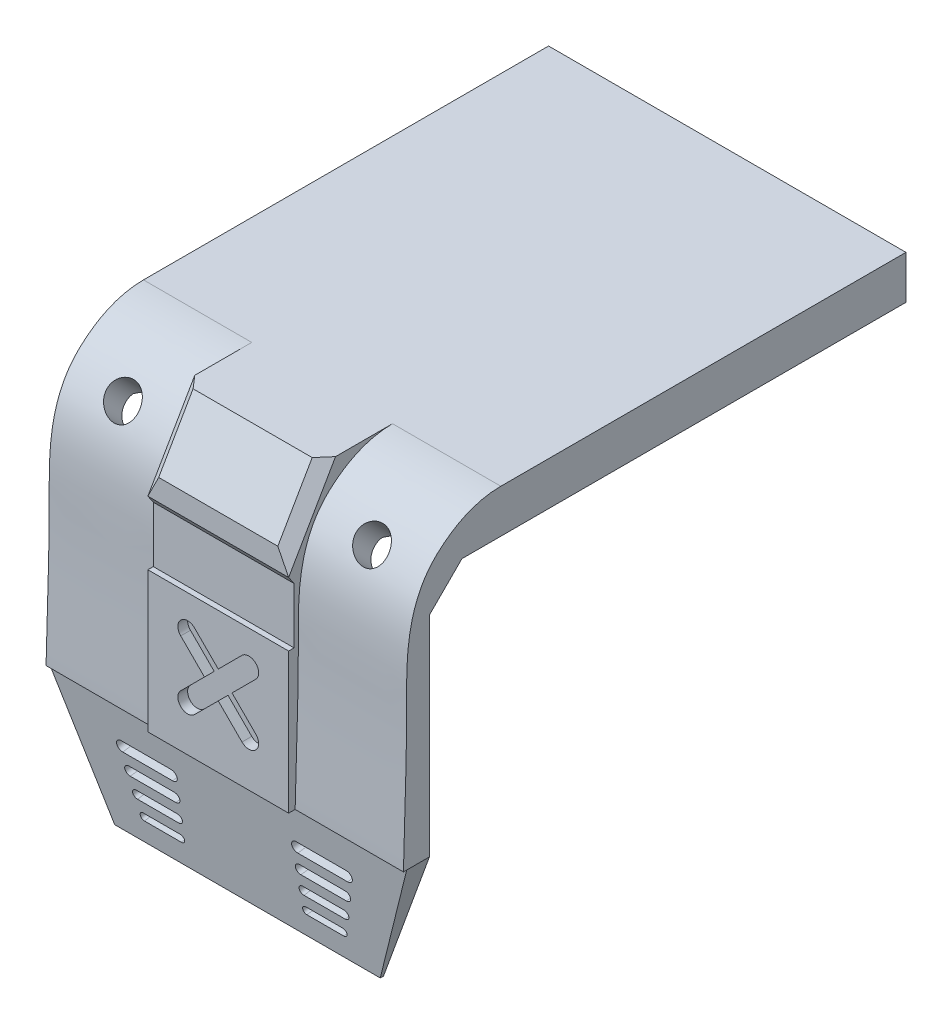
SolidWorks part; units mm, degrees
ref_plane "前视基准面" through (0, 0, 0) normal (0, 0, 1) x (1, 0, 0)
ref_plane "上视基准面" through (0, 0, 0) normal (0, 1, 0) x (1, 0, 0)
ref_plane "右视基准面" through (0, 0, 0) normal (1, 0, 0) x (0, 0, -1)
sketch "草图1" plane through (0, 0, 0) normal (0, 1, 0) x (1, 0, 0)
  line L1 (16.5, -12) -> (-16.5, -12)
  line L2 (16.5, -12) -> (16.5, 12)
  line L3 (16.5, 12) -> (-16.5, 12)
  line L4 (-16.5, -12) -> (-16.5, 12)
  line L5 (16.5, -12) -> (-16.5, 12) construction
  line L6 (16.5, 12) -> (-16.5, -12) construction
  point P0 (0, 0)
  dimension "D1" = 33
  dimension "D2" = 24
extrude "凸台-拉伸1" add sketch "草图1" along normal blind 38
sketch "草图2" plane through (-16.5, 0, 0) normal (-1, 0, 0) x (0, 0, 1)
  line L0 (-12, 33) -> (9, 33)
  line L1 (-12, 38) -> (-12, 0) construction
  line L2 (9, 33) -> (9, 0)
  line L3 (-12, 0) -> (12, 0) construction
  line L4 (9, 0) -> (-12, 0)
  line L5 (-12, 0) -> (-12, 33)
  line L6 (-12, 38) -> (12, 38) construction
  line L7 (12, 38) -> (12, 0) construction
  dimension "D1" = 5
  dimension "D2" = 3
extrude "切除-拉伸1" cut sketch "草图2" against normal blind 35
chamfer "倒角1" distance 5.5 angle 30 1 edges at (0, 38, 12)
chamfer "倒角2" distance 2 angle 45 1 edges at (0, 33, 9)
chamfer "倒角3" distance 1 angle 45 2 edges at (16.5, 33, -2.5) (-16.5, 33, -2.5)
sketch "草图3" plane through (-16.5, 0, 0) normal (-1, 0, 0) x (0, 0, 1)
  line L0 (12, 11.6526) -> (11.1, 11.6526)
  line L1 (12, 32.5) -> (12, 0) construction
  line L2 (11.1, 11.6526) -> (9.3, 0)
  line L3 (9, 0) -> (12, 0) construction
  line L4 (9.3, 0) -> (12, 0)
  line L5 (12, 0) -> (12, 11.6526)
  dimension "D1" = 0.9
  dimension "D2" = 0.3
extrude "切除-拉伸2" cut sketch "草图3" against normal blind 35
sketch "草图4" plane through (-16.5, 0, 0) normal (-1, 0, 0) x (0, 0, 1)
  line L0 (-12, 38) -> (8.8246, 38) construction
  line L1 (2.4074, 38) -> (8.8246, 38)
  line L2 (8.8246, 38) -> (12, 32.5)
  line L6 (12, 32.5) -> (12, 11.6526)
  line L7 (12, 11.6526) -> (11.4, 11.6526)
  spline S0 degree 3 poles (2.4074, 38) (4.9446, 38) (7.5567, 36.3443) (10.7301, 32.9821) (11.1498, 28.4683) (11.0414, 20.8883) (11.4, 13.3386) (11.4, 11.6526) knots 0 0 0 0 0.11289 0.156477 0.404831 0.492287 1 1 1 1
  dimension "D1" = 0.6
extrude "切除-拉伸3" cut sketch "草图4" against normal blind 10
mirror "镜向1" about plane through (0, 0, 0) normal (1, 0, 0) of "切除-拉伸3"
sketch "草图6" plane through (0, 0, 9) normal (0, 0, -1) x (-1, 0, 0)
  line L0 (19.0092, 11.6526) -> (-21.5597, 11.6526) construction
  line L1 (-6.5, 11.6526) -> (6.5, 11.6526) construction
  line L2 (16.5, 11.6526) -> (12.2588, 0)
  line L3 (16.5, 0) -> (-16.5, 0) construction
  line L4 (12.2588, 0) -> (16.5, 0)
  line L5 (16.5, 0) -> (16.5, 11.6526)
  line L6 (0, 0) -> (0, 18.5303) construction
  line L7 (-12.2588, 0) -> (-16.5, 0)
  line L8 (-16.5, 11.6526) -> (-12.2588, 0)
  line L9 (-16.5, 0) -> (-16.5, 11.6526)
  line L10 (16.5, 0) -> (16.5, 31) construction
  dimension "D1" = 20
extrude "切除-拉伸4" cut sketch "草图6" against normal through all
sketch "草图7" plane through (0, 0, 12) normal (0, 0, 1) x (1, 0, 0)
  line L0 (-2.8284, 15.8242) -> (2.8284, 21.4811) construction
  line L1 (-3.4648, 16.4606) -> (2.192, 22.1175)
  line L2 (-2.192, 15.1878) -> (3.4648, 20.8447)
  line L3 (-2.8284, 21.4811) -> (2.8284, 15.8242) construction
  line L4 (-2.192, 22.1175) -> (3.4648, 16.4606)
  line L5 (-3.4648, 20.8447) -> (2.192, 15.1878)
  line L6 (0, 11.6526) -> (0, 25.4332) construction
  line L7 (6.5, 11.6526) -> (-6.5, 11.6526) construction
  arc A0 (-3.4648, 16.4606) -> (-2.192, 15.1878) centre (-2.8284, 15.8242) ccw
  arc A1 (3.4648, 20.8447) -> (2.192, 22.1175) centre (2.8284, 21.4811) ccw
  arc A2 (-2.192, 22.1175) -> (-3.4648, 20.8447) centre (-2.8284, 21.4811) ccw
  arc A3 (2.192, 15.1878) -> (3.4648, 16.4606) centre (2.8284, 15.8242) ccw
  point P2 (0, 18.6526)
  point P7 (0, 18.6526)
  dimension "D1" = 8
  dimension "D2" = 7
  dimension "D3" = 1.8
sketch "草图8" plane through (0, 0, -12) normal (0, 0, -1) x (-1, 0, 0)
  line L6 (-16.5, 38) -> (-16.5, 34)
  line L7 (-16.5, 34) -> (-15.5, 33)
  line L8 (-15.5, 33) -> (15.5, 33)
  line L9 (15.5, 33) -> (16.5, 34)
  line L10 (16.5, 34) -> (16.5, 38)
  line L11 (16.5, 38) -> (-16.5, 38)
  line L12 (-16.5, 38) -> (-16.5, 34)
  line L13 (-16.5, 34) -> (-15.5, 33)
  line L14 (-15.5, 33) -> (15.5, 33)
  line L15 (15.5, 33) -> (16.5, 34)
  line L16 (16.5, 34) -> (16.5, 38)
  line L17 (16.5, 38) -> (-16.5, 38)
  dimension "D1" = 0
extrude "凸台-拉伸4" add sketch "草图8" along normal blind 23
chamfer "倒角4" distance 1 angle 45 2 edges at (-6.5, 35.25, 10.4123) (6.5, 35.25, 10.4123)
sketch "草图9" plane through (0, -1.4031, 9.0833) normal (0, -0.1527, 0.9883) x (1, 0, 0)
  line L0 (-10.3833, 9.3197) -> (-5.7833, 9.3197) construction
  line L3 (-10.3833, 9.8197) -> (-5.7833, 9.8197)
  line L6 (-10.3833, 8.8197) -> (-5.7833, 8.8197)
  line L9 (-7.0299, -0.703) -> (-8.4476, 12.7851) construction
  line L12 (0, 1.4197) -> (0, 15.4722) construction
  line L13 (12.2588, 1.4197) -> (-12.2588, 1.4197) construction
  line L14 (-9.9784, 7.3697) -> (-5.7784, 7.3697) construction
  line L15 (-9.9784, 7.8197) -> (-5.7784, 7.8197)
  line L16 (-9.9784, 6.9197) -> (-5.7784, 6.9197)
  line L17 (-9.5839, 5.5197) -> (-5.7839, 5.5197) construction
  line L18 (-9.5839, 5.9197) -> (-5.7839, 5.9197)
  line L19 (-9.5839, 5.1197) -> (-5.7839, 5.1197)
  line L20 (-9.2, 3.7697) -> (-5.8, 3.7697) construction
  line L21 (-9.2, 4.1197) -> (-5.8, 4.1197)
  line L22 (-9.2, 3.4197) -> (-5.8, 3.4197)
  line L23 (9.2, 3.7697) -> (5.8, 3.7697) construction
  line L24 (9.2, 4.1197) -> (5.8, 4.1197)
  line L25 (9.2, 3.4197) -> (5.8, 3.4197)
  line L26 (9.5839, 5.5197) -> (5.7839, 5.5197) construction
  line L27 (9.5839, 5.9197) -> (5.7839, 5.9197)
  line L28 (9.5839, 5.1197) -> (5.7839, 5.1197)
  line L29 (9.9784, 7.3697) -> (5.7784, 7.3697) construction
  line L30 (9.9784, 7.8197) -> (5.7784, 7.8197)
  line L31 (9.9784, 6.9197) -> (5.7784, 6.9197)
  line L32 (10.3833, 9.3197) -> (5.7833, 9.3197) construction
  line L33 (10.3833, 9.8197) -> (5.7833, 9.8197)
  line L34 (10.3833, 8.8197) -> (5.7833, 8.8197)
  arc A8 (-10.3833, 9.8197) -> (-10.3833, 8.8197) centre (-10.3833, 9.3197) ccw
  arc A9 (-5.7833, 8.8197) -> (-5.7833, 9.8197) centre (-5.7833, 9.3197) ccw
  arc A10 (-9.9784, 7.8197) -> (-9.9784, 6.9197) centre (-9.9784, 7.3697) ccw
  arc A11 (-5.7784, 6.9197) -> (-5.7784, 7.8197) centre (-5.7784, 7.3697) ccw
  arc A12 (-9.5839, 5.9197) -> (-9.5839, 5.1197) centre (-9.5839, 5.5197) ccw
  arc A13 (-5.7839, 5.1197) -> (-5.7839, 5.9197) centre (-5.7839, 5.5197) ccw
  arc A14 (-9.2, 4.1197) -> (-9.2, 3.4197) centre (-9.2, 3.7697) ccw
  arc A15 (-5.8, 3.4197) -> (-5.8, 4.1197) centre (-5.8, 3.7697) ccw
  arc A16 (9.2, 4.1197) -> (9.2, 3.4197) centre (9.2, 3.7697) cw
  arc A17 (5.8, 3.4197) -> (5.8, 4.1197) centre (5.8, 3.7697) cw
  arc A18 (9.5839, 5.9197) -> (9.5839, 5.1197) centre (9.5839, 5.5197) cw
  arc A19 (5.7839, 5.1197) -> (5.7839, 5.9197) centre (5.7839, 5.5197) cw
  arc A20 (9.9784, 7.8197) -> (9.9784, 6.9197) centre (9.9784, 7.3697) cw
  arc A21 (5.7784, 6.9197) -> (5.7784, 7.8197) centre (5.7784, 7.3697) cw
  arc A22 (10.3833, 9.8197) -> (10.3833, 8.8197) centre (10.3833, 9.3197) cw
  arc A23 (5.7833, 8.8197) -> (5.7833, 9.8197) centre (5.7833, 9.3197) cw
  point P2 (-8.0833, 9.3197)
  point P15 (-7.8784, 7.3697)
  point P20 (-7.6839, 5.5197)
  point P27 (-7.5, 3.7697)
  point P43 (7.5, 3.7697)
  point P50 (7.6839, 5.5197)
  point P57 (7.8784, 7.3697)
  point P64 (8.0833, 9.3197)
  dimension "D1" = 1
  dimension "D2" = 4.6
  dimension "D3" = 7.5
  dimension "D4" = 0.9
  dimension "D5" = 4.2
  dimension "D6" = 1
  dimension "D7" = 0.8
  dimension "D8" = 3.8
  dimension "D9" = 1
  dimension "D10" = 0.7
  dimension "D11" = 3.4
  dimension "D12" = 1
  dimension "D13" = 2
  dimension "D14" = 96
extrude "切除-拉伸5" cut sketch "草图9" against normal through all
extrude "切除-拉伸6" cut sketch "草图7" against normal blind 0.9 contours L4 A2 L5 L1 | L2 A1 L1 L4 | L1 L5 L2 L4 | L5 A3 L4 L2 | L1 A0 L2 L5
sketch "草图14" plane through (6.5, 0, 0) normal (1, 0, 0) x (0, 0, -1)
  line L0 (-12, 24.6181) -> (-11.4986, 24.6181)
  line L1 (-12, 11.6526) -> (-12, 30.5) construction
  line L2 (-11.4986, 24.6181) -> (-11.4986, 29.7685)
  line L3 (-11.4986, 29.7685) -> (-12, 30.5)
  line L4 (-12, 30.5) -> (-12, 24.6181)
extrude "切除-拉伸10" cut sketch "草图14" against normal through all
sketch "草图11" plane through (0, 20, 20) normal (0, -0.7071, -0.7071) x (1, 0, 0)
  line L0 (0, 0) -> (0, -28.6759) construction
  line L1 (-6.5, -25.1678) -> (-16.5, -25.1678) construction
  circle A0 centre (-11.5, -17.6678) radius 1.55
  circle A1 centre (11.5, -17.6678) radius 1.55
  dimension "D1" = 3.1
  dimension "D2" = 11.5
  dimension "D3" = 7.5
extrude "切除-拉伸11" cut sketch "草图11" against normal through all and the other way through all
